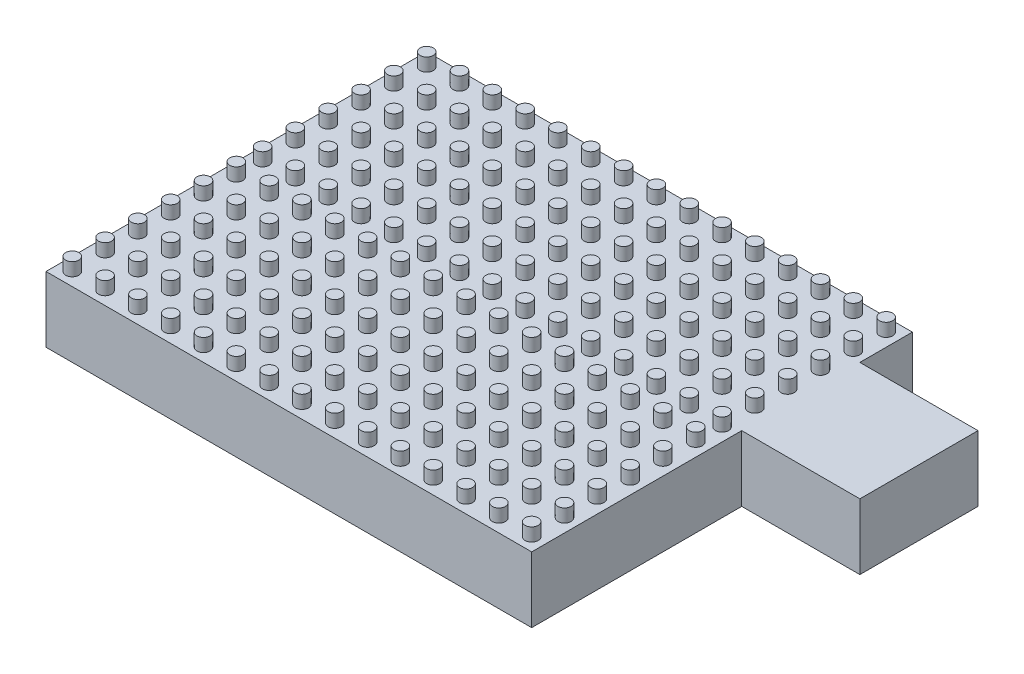
SolidWorks part; units mm, degrees
ref_plane "前视基准面" through (0, 0, 0) normal (0, 0, 1) x (1, 0, 0)
ref_plane "上视基准面" through (0, 0, 0) normal (0, 1, 0) x (1, 0, 0)
ref_plane "右视基准面" through (0, 0, 0) normal (1, 0, 0) x (0, 0, -1)
other "Configuration Table"
sketch "草图1" plane through (0, 0, 0) normal (0, 1, 0) x (1, 0, 0)
  line L1 (-370, 290) -> (370, 290)
  line L2 (-370, 290) -> (-370, -290)
  line L3 (-370, -290) -> (370, -290)
  line L4 (370, 290) -> (370, -290)
  line L5 (-370, 290) -> (370, -290) construction
  line L6 (-370, -290) -> (370, 290) construction
  point P0 (0, 0)
  dimension "D1" = 740
  dimension "D2" = 580
extrude "凸台-拉伸1" add sketch "草图1" along normal blind 100
ref_plane "基准面1" through (0, 100, 0) normal (0, 1, 0) x (1, 0, 0)
sketch "草图2" plane through (0, 100, 0) normal (0, 1, 0) x (1, 0, 0)
  line L4 (370, -290) -> (370, 290)
  line L5 (370, 290) -> (-370, 290)
  line L6 (-370, 290) -> (-370, -290)
  line L7 (-370, -290) -> (370, -290)
  line L8 (370, -290) -> (370, 290) construction
  line L9 (370, 290) -> (-370, 290) construction
  line L10 (-370, 290) -> (-370, -290) construction
  line L11 (-370, -290) -> (370, -290) construction
  circle A0 centre (-350, 270) radius 10
  circle A1 centre (-300, 270) radius 10
  circle A2 centre (-250, 270) radius 10
  circle A3 centre (-200, 270) radius 10
  circle A4 centre (-150, 270) radius 10
  circle A5 centre (-100, 270) radius 10
  circle A6 centre (-50, 270) radius 10
  circle A7 centre (0, 270) radius 10
  circle A8 centre (50, 270) radius 10
  circle A9 centre (100, 270) radius 10
  circle A10 centre (150, 270) radius 10
  circle A11 centre (200, 270) radius 10
  circle A12 centre (250, 270) radius 10
  circle A13 centre (300, 270) radius 10
  circle A14 centre (350, 270) radius 10
  circle A15 centre (-300, 220) radius 10
  circle A16 centre (-250, 220) radius 10
  circle A17 centre (-200, 220) radius 10
  circle A18 centre (-150, 220) radius 10
  circle A19 centre (-100, 220) radius 10
  circle A20 centre (-50, 220) radius 10
  circle A21 centre (0, 220) radius 10
  circle A22 centre (50, 220) radius 10
  circle A23 centre (100, 220) radius 10
  circle A24 centre (150, 220) radius 10
  circle A25 centre (200, 220) radius 10
  circle A26 centre (250, 220) radius 10
  circle A27 centre (300, 220) radius 10
  circle A28 centre (350, 220) radius 10
  circle A29 centre (-300, 170) radius 10
  circle A30 centre (-250, 170) radius 10
  circle A31 centre (-200, 170) radius 10
  circle A32 centre (-150, 170) radius 10
  circle A33 centre (-100, 170) radius 10
  circle A34 centre (-50, 170) radius 10
  circle A35 centre (0, 170) radius 10
  circle A36 centre (50, 170) radius 10
  circle A37 centre (100, 170) radius 10
  circle A38 centre (150, 170) radius 10
  circle A39 centre (200, 170) radius 10
  circle A40 centre (250, 170) radius 10
  circle A41 centre (300, 170) radius 10
  circle A42 centre (350, 170) radius 10
  circle A43 centre (-300, 120) radius 10
  circle A44 centre (-250, 120) radius 10
  circle A45 centre (-200, 120) radius 10
  circle A46 centre (-150, 120) radius 10
  circle A47 centre (-100, 120) radius 10
  circle A48 centre (-50, 120) radius 10
  circle A49 centre (0, 120) radius 10
  circle A50 centre (50, 120) radius 10
  circle A51 centre (100, 120) radius 10
  circle A52 centre (150, 120) radius 10
  circle A53 centre (200, 120) radius 10
  circle A54 centre (250, 120) radius 10
  circle A55 centre (300, 120) radius 10
  circle A56 centre (350, 120) radius 10
  circle A57 centre (-300, 70) radius 10
  circle A58 centre (-250, 70) radius 10
  circle A59 centre (-200, 70) radius 10
  circle A60 centre (-150, 70) radius 10
  circle A61 centre (-100, 70) radius 10
  circle A62 centre (-50, 70) radius 10
  circle A63 centre (0, 70) radius 10
  circle A64 centre (50, 70) radius 10
  circle A65 centre (100, 70) radius 10
  circle A66 centre (150, 70) radius 10
  circle A67 centre (200, 70) radius 10
  circle A68 centre (250, 70) radius 10
  circle A69 centre (300, 70) radius 10
  circle A70 centre (350, 70) radius 10
  circle A71 centre (-300, 20) radius 10
  circle A72 centre (-250, 20) radius 10
  circle A73 centre (-200, 20) radius 10
  circle A74 centre (-150, 20) radius 10
  circle A75 centre (-100, 20) radius 10
  circle A76 centre (-50, 20) radius 10
  circle A77 centre (0, 20) radius 10
  circle A78 centre (50, 20) radius 10
  circle A79 centre (100, 20) radius 10
  circle A80 centre (150, 20) radius 10
  circle A81 centre (200, 20) radius 10
  circle A82 centre (250, 20) radius 10
  circle A83 centre (300, 20) radius 10
  circle A84 centre (350, 20) radius 10
  circle A85 centre (-350, 220) radius 10
  circle A86 centre (-350, 170) radius 10
  circle A87 centre (-350, 120) radius 10
  circle A88 centre (-350, 70) radius 10
  circle A89 centre (-350, 20) radius 10
  circle A90 centre (350, -270) radius 10
  circle A91 centre (300, -270) radius 10
  circle A92 centre (250, -270) radius 10
  circle A93 centre (200, -270) radius 10
  circle A94 centre (150, -270) radius 10
  circle A95 centre (100, -270) radius 10
  circle A96 centre (50, -270) radius 10
  circle A97 centre (0, -270) radius 10
  circle A98 centre (-50, -270) radius 10
  circle A99 centre (-100, -270) radius 10
  circle A100 centre (-150, -270) radius 10
  circle A101 centre (-200, -270) radius 10
  circle A102 centre (-250, -270) radius 10
  circle A103 centre (-300, -270) radius 10
  circle A104 centre (-350, -270) radius 10
  circle A105 centre (300, -220) radius 10
  circle A106 centre (250, -220) radius 10
  circle A107 centre (200, -220) radius 10
  circle A108 centre (150, -220) radius 10
  circle A109 centre (100, -220) radius 10
  circle A110 centre (50, -220) radius 10
  circle A111 centre (0, -220) radius 10
  circle A112 centre (-50, -220) radius 10
  circle A113 centre (-100, -220) radius 10
  circle A114 centre (-150, -220) radius 10
  circle A115 centre (-200, -220) radius 10
  circle A116 centre (-250, -220) radius 10
  circle A117 centre (-300, -220) radius 10
  circle A118 centre (-350, -220) radius 10
  circle A119 centre (300, -170) radius 10
  circle A120 centre (250, -170) radius 10
  circle A121 centre (200, -170) radius 10
  circle A122 centre (150, -170) radius 10
  circle A123 centre (100, -170) radius 10
  circle A124 centre (50, -170) radius 10
  circle A125 centre (0, -170) radius 10
  circle A126 centre (-50, -170) radius 10
  circle A127 centre (-100, -170) radius 10
  circle A128 centre (-150, -170) radius 10
  circle A129 centre (-200, -170) radius 10
  circle A130 centre (-250, -170) radius 10
  circle A131 centre (-300, -170) radius 10
  circle A132 centre (-350, -170) radius 10
  circle A133 centre (300, -120) radius 10
  circle A134 centre (250, -120) radius 10
  circle A135 centre (200, -120) radius 10
  circle A136 centre (150, -120) radius 10
  circle A137 centre (100, -120) radius 10
  circle A138 centre (50, -120) radius 10
  circle A139 centre (0, -120) radius 10
  circle A140 centre (-50, -120) radius 10
  circle A141 centre (-100, -120) radius 10
  circle A142 centre (-150, -120) radius 10
  circle A143 centre (-200, -120) radius 10
  circle A144 centre (-250, -120) radius 10
  circle A145 centre (-300, -120) radius 10
  circle A146 centre (-350, -120) radius 10
  circle A147 centre (300, -70) radius 10
  circle A148 centre (250, -70) radius 10
  circle A149 centre (200, -70) radius 10
  circle A150 centre (150, -70) radius 10
  circle A151 centre (100, -70) radius 10
  circle A152 centre (50, -70) radius 10
  circle A153 centre (0, -70) radius 10
  circle A154 centre (-50, -70) radius 10
  circle A155 centre (-100, -70) radius 10
  circle A156 centre (-150, -70) radius 10
  circle A157 centre (-200, -70) radius 10
  circle A158 centre (-250, -70) radius 10
  circle A159 centre (-300, -70) radius 10
  circle A160 centre (-350, -70) radius 10
  circle A161 centre (300, -20) radius 10
  circle A162 centre (250, -20) radius 10
  circle A163 centre (200, -20) radius 10
  circle A164 centre (150, -20) radius 10
  circle A165 centre (100, -20) radius 10
  circle A166 centre (50, -20) radius 10
  circle A167 centre (0, -20) radius 10
  circle A168 centre (-50, -20) radius 10
  circle A169 centre (-100, -20) radius 10
  circle A170 centre (-150, -20) radius 10
  circle A171 centre (-200, -20) radius 10
  circle A172 centre (-250, -20) radius 10
  circle A173 centre (-300, -20) radius 10
  circle A174 centre (-350, -20) radius 10
  circle A175 centre (350, -220) radius 10
  circle A176 centre (350, -170) radius 10
  circle A177 centre (350, -120) radius 10
  circle A178 centre (350, -70) radius 10
  circle A179 centre (350, -20) radius 10
  dimension "D2" = 20
  dimension "D9" = 20
  dimension "D3" = 20
  dimension "D4" = 20
  dimension "D7" = 20
  dimension "D8" = 20
  dimension "D1" = 0
  dimension "D5" = 15
  dimension "D6" = 6
  dimension "D10" = 15
  dimension "D11" = 6
extrude "凸台-拉伸3" add sketch "草图2" along normal blind 20
ref_plane "基准面2" through (370, 0, 0) normal (-1, 0, 0) x (0, 0, 1)
sketch "草图3" plane through (370, 0, 0) normal (-1, 0, 0) x (0, 0, 1)
  line L0 (-290, 50) -> (290, 50) construction
  line L1 (0, 100) -> (0, 0) construction
  line L3 (-210, 100) -> (-30, 100)
  line L4 (-290, 0) -> (290, 0)
  line L5 (290, 0) -> (290, 100)
  line L6 (290, 100) -> (-290, 100)
  line L7 (-290, 100) -> (-290, 0)
  line L8 (-290, 0) -> (290, 0) construction
  line L9 (290, 0) -> (290, 100) construction
  line L10 (290, 100) -> (-290, 100) construction
  line L11 (-290, 100) -> (-290, 0) construction
  line L12 (-210, 100) -> (-210, 0)
  line L13 (-210, 0) -> (-30, 0)
  line L14 (-30, 100) -> (-30, 0)
  line L15 (-210, 100) -> (-30, 0) construction
  line L16 (-210, 0) -> (-30, 100) construction
  point P9 (-120, 50)
  dimension "D2" = 100
  dimension "D3" = 180
  dimension "D4" = 80
  dimension "D1" = 0
extrude "凸台-拉伸4" add sketch "草图3" against normal blind 180
